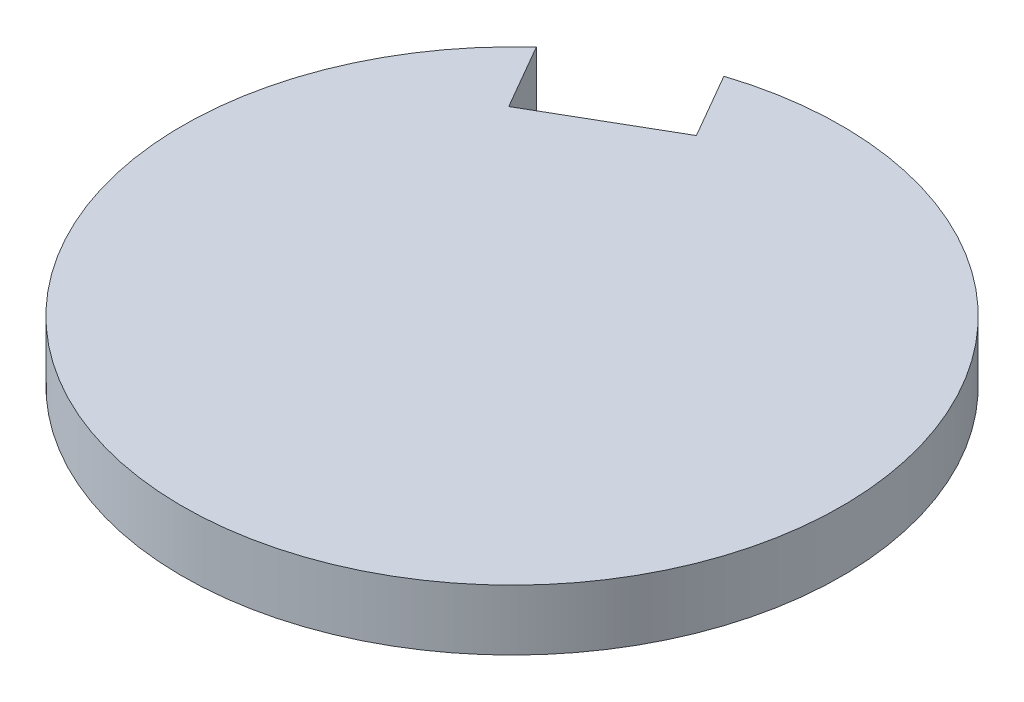
SolidWorks part; units mm, degrees
ref_plane "Front Plane" through (0, 0, 0) normal (0, 0, 1) x (1, 0, 0)
ref_plane "Top Plane" through (0, 0, 0) normal (0, 1, 0) x (1, 0, 0)
ref_plane "Right Plane" through (0, 0, 0) normal (1, 0, 0) x (0, 0, -1)
sketch "Sketch4" plane through (0, 0, 0) normal (0, 1, 0) x (1, 0, 0)
  circle A0 centre (0, 0) radius 152.4
  dimension "D1" = 304.8
extrude "Boss-Extrude1" add sketch "Sketch4" along normal blind 14 and the other way blind 14
sketch "Sketch6" plane through (0, 14, 0) normal (0, 1, 0) x (1, 0, 0)
  line L0 (0, 0) -> (0, 152.4)
  line L1 (0, 0) -> (131.9823, 76.2)
  line L2 (0, 0) -> (131.9823, -76.2)
  line L3 (0, 0) -> (0, -152.4)
  line L4 (0, 0) -> (-131.9823, -76.2)
  line L5 (0, 0) -> (-131.9823, 76.2)
  circle A0 centre (0, 0) radius 152.4 construction
  point P12 (0, 0)
  dimension "D1" = 6
sketch "Sketch7" plane through (0, 14, 0) normal (0, 1, 0) x (1, 0, 0)
  line L0 (0, 0) -> (-131.9823, 76.2) construction
  line L1 (0, 0) -> (-76.2, 131.9823) construction
  line L2 (-48.7037, 147.8573) -> (-103.6963, 116.1073)
  line L3 (-103.6963, 116.1073) -> (-84.6463, 83.1117)
  line L4 (-84.6463, 83.1117) -> (-29.6537, 114.8617)
  line L5 (-29.6537, 114.8617) -> (-48.7037, 147.8573)
  arc A0 (0, 152.4) -> (-131.9823, 76.2) centre (0, 0) ccw construction
  point P11 (-76.2, 131.9823)
  dimension "D2" = 38.1
  dimension "D1" = 63.5
extrude "Cut-Extrude2" cut sketch "Sketch7" against normal through all both and the other way through all
ref_plane "Plane1" through (0, 0, 0) normal (0.866, 0, -0.5) x (-0.5, 0, -0.866)
sketch "Sketch9" plane through (0, 0, 0) normal (0.866, 0, -0.5) x (-0.5, 0, -0.866)
  line L0 (149.056, 14) -> (114.3, -14) construction
  line L1 (131.678, 0) -> (134.218, 0) construction
  circle A0 centre (134.218, 0) radius 8.89
  dimension "D2" = 17.78
  dimension "D1" = 2.54
extrude "Cut-Extrude4" cut sketch "Sketch9" along normal blind 41.91
